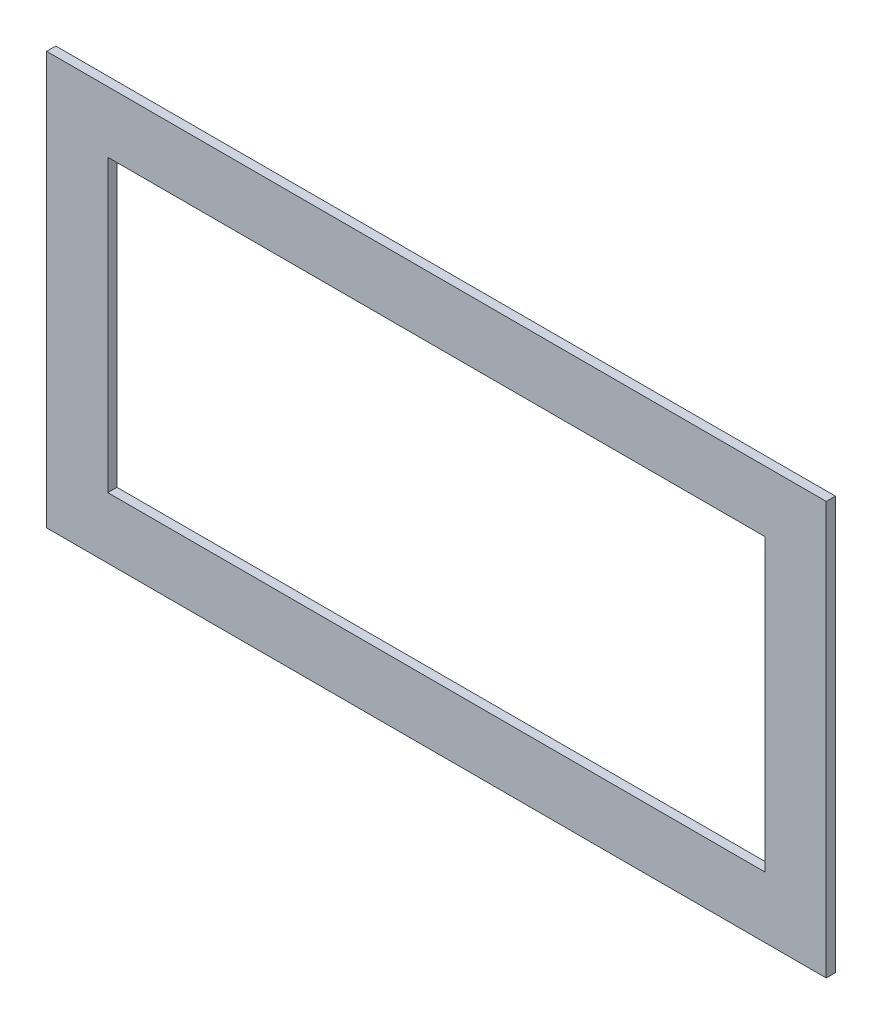
SolidWorks part; units mm, degrees
ref_plane "Front Plane" through (0, 0, 0) normal (0, 0, 1) x (1, 0, 0)
ref_plane "Top Plane" through (0, 0, 0) normal (0, 1, 0) x (1, 0, 0)
ref_plane "Right Plane" through (0, 0, 0) normal (1, 0, 0) x (0, 0, -1)
sketch "Sketch1" plane through (0, 0, 0) normal (0, 0, 1) x (1, 0, 0)
  line L0 (5, 130) -> (5, 127) construction
  line L1 (-250, 130) -> (5, 130) construction
  line L2 (-250, 130) -> (-250, 127) construction
  line L3 (-250, 127) -> (-250, -2) construction
  line L4 (-250, -2) -> (-250, -5) construction
  line L5 (5, -5) -> (-250, -5) construction
  line L6 (5, -2) -> (5, -5) construction
  line L7 (5, -2) -> (5, 127) construction
  line L8 (5, 130) -> (5, 127)
  line L9 (-250, 130) -> (5, 130)
  line L10 (-250, 130) -> (-250, 127)
  line L11 (-250, 127) -> (-250, -2)
  line L12 (-250, -2) -> (-250, -5)
  line L13 (5, -5) -> (-250, -5)
  line L14 (5, -2) -> (5, -5)
  line L15 (5, -2) -> (5, 127)
  line L17 (-15, 110) -> (-230, 110)
  line L18 (-15, 110) -> (-15, 15)
  line L19 (-15, 15) -> (-230, 15)
  line L20 (-230, 110) -> (-230, 15)
  dimension "D1" = 20
  dimension "D2" = 20
  dimension "D3" = 20
  dimension "D4" = 20
extrude "Boss-Extrude1" add sketch "Sketch1" along normal blind 3
